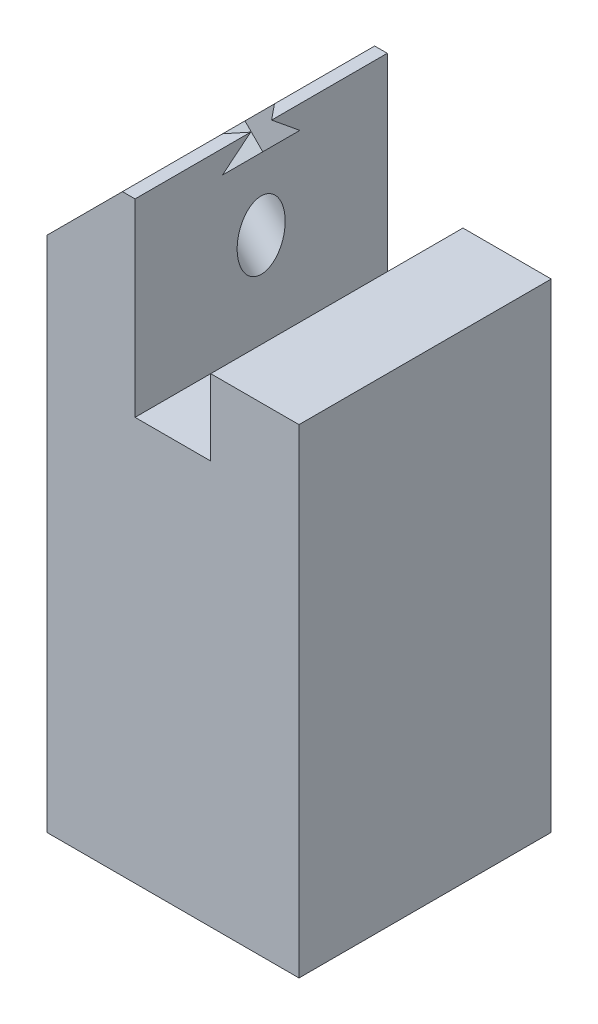
SolidWorks part; units mm, degrees
ref_plane "Front Plane" through (0, 0, 0) normal (0, 0, 1) x (1, 0, 0)
ref_plane "Top Plane" through (0, 0, 0) normal (0, 1, 0) x (1, 0, 0)
ref_plane "Right Plane" through (0, 0, 0) normal (1, 0, 0) x (0, 0, -1)
sketch "Sketch1" plane through (0, 0, 0) normal (0, 1, 0) x (1, 0, 0)
  line L1 (-10, -10) -> (10, -10)
  line L2 (-10, -10) -> (-10, 10)
  line L3 (-10, 10) -> (10, 10)
  line L4 (10, -10) -> (10, 10)
  line L5 (-10, -10) -> (10, 10) construction
  line L6 (-10, 10) -> (10, -10) construction
  point P0 (0, 0)
extrude "Boss-Extrude1" add sketch "Sketch1" along normal blind 6
sketch "Sketch2" plane through (0, 6, 0) normal (0, 1, 0) x (1, 0, 0)
  line L0 (10, 0) -> (3, 0) construction
  line L1 (10, -10) -> (10, 10) construction
  line L2 (-10, -10) -> (10, -10) construction
  line L3 (3, -10) -> (10, -10)
  line L4 (3, -10) -> (3, 10)
  line L5 (3, 10) -> (10, 10)
  line L6 (10, -10) -> (10, 10)
extrude "Boss-Extrude2" add sketch "Sketch2" along normal blind 6
sketch "Sketch3" plane through (0, 6, 0) normal (0, 1, 0) x (1, 0, 0)
  line L0 (-10, 0) -> (-3, 0) construction
  line L1 (-10, 10) -> (-10, -10) construction
  line L2 (3, 10) -> (-10, 10) construction
  line L3 (-10, -10) -> (-3, -10)
  line L4 (-10, -10) -> (-10, 10)
  line L5 (-10, 10) -> (-3, 10)
  line L6 (-3, -10) -> (-3, 10)
extrude "Boss-Extrude3" add sketch "Sketch3" along normal blind 15
chamfer "Chamfer1" distance 6 angle 45 1 edges at (-10, 21, 0)
sketch "Sketch4" plane through (-12.5, 12.5, 0) normal (-0.7071, 0.7071, 0) x (0, 0, 1)
  line L0 (0, 3.5355) -> (0, 5.4132) construction
  line L1 (10, 3.5355) -> (-10, 3.5355) construction
  line L2 (0, 5.4132) -> (0, 7.4325) construction
  circle A0 centre (0, 7.4325) radius 1.905
extrude "Cut-Extrude1" cut sketch "Sketch4" against normal blind 10 contours A0
sketch "Sketch5" plane through (0, 0, 0) normal (0, -1, 0) x (1, 0, 0)
  line L1 (10, -10) -> (-10, -10)
  line L2 (10, -10) -> (10, 10)
  line L3 (10, 10) -> (-10, 10)
  line L4 (-10, -10) -> (-10, 10)
  line L5 (10, -10) -> (-10, 10) construction
  line L6 (10, 10) -> (-10, -10) construction
  point P0 (0, 0)
extrude "Boss-Extrude4" add sketch "Sketch5" along normal blind 26
sketch "Sketch6" plane through (-12.5, 12.5, 0) normal (-0.7071, 0.7071, 0) x (0, 0, 1)
  line L1 (0, 13.206) -> (-5, 10.3193)
  line L2 (-5, 10.3193) -> (-5, 4.5458)
  line L3 (-5, 4.5458) -> (0, 1.659)
  line L4 (0, 1.659) -> (5, 4.5458)
  line L5 (5, 4.5458) -> (5, 10.3193)
  line L6 (5, 10.3193) -> (0, 13.206)
  circle A0 centre (0, 7.4325) radius 5 construction
extrude "Cut-Extrude2" cut sketch "Sketch6" against normal blind 2 contours L1 L2 L3 L4 L5 L6
sketch "Sketch7" plane through (0, -26, 0) normal (0, -1, 0) x (-1, 0, 0)
  circle A0 centre (0, 0) radius 2.75
extrude "Cut-Extrude3" cut sketch "Sketch7" against normal blind 20
sketch "Sketch8" plane through (0, -26, 0) normal (0, -1, 0) x (-1, 0, 0)
  line L1 (5.4876, -3.1968) -> (5.5123, 3.154)
  line L2 (5.5123, 3.154) -> (0.0247, 6.3508)
  line L3 (0.0247, 6.3508) -> (-5.4876, 3.1968)
  line L4 (-5.4876, 3.1968) -> (-5.5123, -3.154)
  line L5 (-5.5123, -3.154) -> (-0.0247, -6.3508)
  line L6 (-0.0247, -6.3508) -> (5.4876, -3.1968)
  circle A0 centre (0, 0) radius 5.5 construction
extrude "Cut-Extrude4" cut sketch "Sketch8" against normal blind 6
